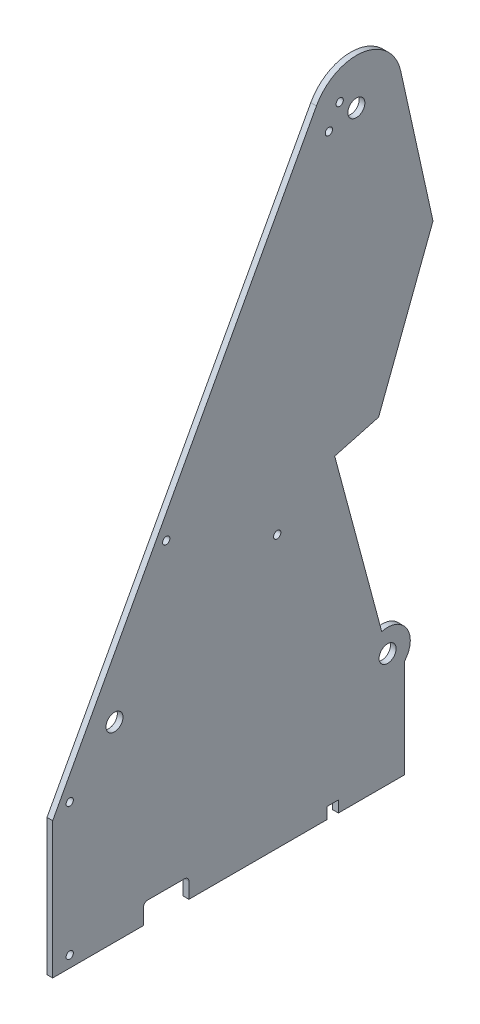
SolidWorks part; units mm, degrees
ref_plane "Front Plane" through (0, 0, 0) normal (0, 0, 1) x (1, 0, 0)
ref_plane "Top Plane" through (0, 0, 0) normal (0, 1, 0) x (1, 0, 0)
ref_plane "Right Plane" through (0, 0, 0) normal (1, 0, 0) x (0, 0, -1)
sketch "Sketch1" plane through (0, 0, 0) normal (1, 0, 0) x (0, 0, -1)
  line L0 (0, 0) -> (0, 55.0997)
  line L6 (-39.108, 173.9053) -> (-14.5735, 180.4793)
  line L7 (-14.5735, 180.4793) -> (15.875, 260.35)
  line L8 (15.875, 260.35) -> (-2.1865, 342.0339)
  line L9 (-49.3231, 348.6446) -> (-196.85, 76.2)
  line L10 (-196.85, 0) -> (0, 0)
  line L11 (-196.85, 76.2) -> (-196.85, 0)
  line L13 (-39.108, 173.9053) -> (-12.812, 75.7673)
  line L14 (-12.812, 75.7673) -> (13.738, 82.8813) construction
  arc A0 (-2.1865, 342.0339) -> (-49.3231, 348.6446) centre (-26.9875, 336.55) ccw
  arc A3 (0, 55.0997) -> (-12.812, 75.7673) centre (-9.525, 63.5) ccw
  dimension "D2" = 25.4
  dimension "D6" = 196.85
  dimension "D7" = 76.2
  dimension "D12" = 12.7
  dimension "D1" = 26.9875
  dimension "D3" = 336.55
  dimension "D4" = 25.4
  dimension "D5" = 101.6
  dimension "D10" = 9.525
  dimension "D11" = 63.5
  dimension "D13" = 76.2
  dimension "D14" = 15.875
  dimension "D15" = 15
extrude "Boss-Extrude1" add sketch "Sketch1" along normal blind 3.175
sketch "Sketch2" plane through (3.175, 0, 0) normal (1, 0, 0) x (0, 0, -1)
  line L16 (-146.05, 8.7909) -> (-146.05, -0.3034) construction
  line L17 (-123.0376, 11.1785) -> (-143.6624, 11.1785) construction
  line L18 (-120.65, -0.3034) -> (-120.65, 8.7909) construction
  line L19 (-146.05, 8.7909) -> (-146.05, 0)
  line L20 (-123.0376, 11.1785) -> (-143.6624, 11.1785)
  line L21 (-120.65, 0) -> (-120.65, 8.7909)
  line L23 (-37.0504, 0) -> (-37.0504, 6.35) construction
  line L24 (-43.4004, 0) -> (-37.0504, 0) construction
  line L25 (-146.05, 0) -> (-120.65, 0)
  line L26 (-196.85, 0) -> (0, 0) construction
  line L27 (-43.4004, 6.35) -> (-43.4004, 0) construction
  line L28 (-37.0504, 6.35) -> (-43.4004, 6.35) construction
  line L29 (-37.0504, 0) -> (-37.0504, 6.35)
  line L30 (-43.4004, 0) -> (-37.0504, 0)
  line L31 (-43.4004, 6.35) -> (-43.4004, 0)
  line L32 (-37.0504, 6.35) -> (-43.4004, 6.35)
  line L33 (-223.2996, 0) -> (-223.2996, 6.35) construction
  line L34 (-229.6496, 0) -> (-223.2996, 0) construction
  line L35 (-229.6496, 6.35) -> (-229.6496, 0) construction
  line L36 (-223.2996, 6.35) -> (-229.6496, 6.35) construction
  line L37 (-223.2996, 0) -> (-223.2996, 6.35)
  line L38 (-229.6496, 0) -> (-223.2996, 0)
  line L39 (-229.6496, 6.35) -> (-229.6496, 0)
  line L40 (-223.2996, 6.35) -> (-229.6496, 6.35)
  arc A0 (-143.6624, 11.1785) -> (-146.05, 8.7909) centre (-143.6624, 8.7909) ccw construction
  arc A1 (-120.65, 8.7909) -> (-123.0376, 11.1785) centre (-123.0376, 8.7909) ccw construction
  arc A2 (-143.6624, 11.1785) -> (-146.05, 8.7909) centre (-143.6624, 8.7909) ccw
  arc A3 (-120.65, 8.7909) -> (-123.0376, 11.1785) centre (-123.0376, 8.7909) ccw
extrude "Cut-Extrude1" cut sketch "Sketch2" against normal through all
sketch "Sketch3" plane through (3.175, 0, 0) normal (1, 0, 0) x (0, 0, -1)
  point P0 (-26.9875, 336.55)
  point P4 (-9.525, 63.5)
hole_wizard "3/8 Clearance Hole1" positions "Sketch3" profile "Sketch4" hole size "3/8" standard "ANSI Inch" end condition up to next
sketch "Sketch4" plane through (3.175, 336.55, 26.9875) normal (0, 1, 0) x (0, 0, -1)
  line L0 (0, 0) -> (0, 3.175)
  line L1 (0, 3.175) -> (4.7625, 3.175)
  line L2 (4.7625, 3.175) -> (4.7625, 0)
  line L5 (4.7625, 0) -> (0, 0)
  line L11 (0, -6.35) -> (0, 107.95) construction
  dimension "Thru Hole Dia." = 9.525
  dimension "Thru Hole Depth" = 3.175
sketch "Sketch5" plane through (3.175, 0, 0) normal (1, 0, 0) x (0, 0, -1)
  line L0 (-9.525, 63.5) -> (26.2895, 27.4728)
  line L1 (26.2895, 27.4728) -> (26.2524, 14.9296)
  line L2 (21.8127, 31.9762) -> (-24.8224, 22.3166)
  line L3 (-15.875, 19.05) -> (-24.8224, 22.3166)
  line L4 (0, 0) -> (0, 55.0997) construction
  line L5 (-15.875, 19.05) -> (-33.1481, 11.0161)
  line L6 (-33.1481, 11.0161) -> (-54.7505, 169.5016)
  line L7 (50.8, 0) -> (50.8, 73.5762) construction
  dimension "D1" = 44.45
  dimension "D2" = 50.8
  dimension "D3" = 45
  dimension "D4" = 60.325
  dimension "D5" = 19.05
  dimension "D6" = 15.875
  dimension "D7" = 9.525
  dimension "D8" = 47.625
  dimension "D9" = 19.05
  dimension "D10" = 45
  dimension "D11" = 50.8
sketch "Sketch6" plane through (3.175, 0, 0) normal (1, 0, 0) x (0, 0, -1)
  line L1 (-162.2756, 106.7109) -> (-176.2354, 114.27) construction
  line L3 (-49.3231, 348.6446) -> (-196.85, 76.2) construction
  circle A2 centre (-162.2756, 106.7109) radius 4.7625
  dimension "D4" = 9.525
  dimension "D5" = 15.875
  dimension "D6" = 266.7
extrude "Cut-Extrude2" cut sketch "Sketch6" against normal through all
sketch "Sketch8" [suppressed] plane through (3.175, 0, 0) normal (1, 0, 0) x (0, 0, -1)
  circle A0 centre (-159.5042, 86.429) radius 4.7625
  circle A1 centre (-165.9449, 66.9082) radius 2.032
  circle A2 centre (-112.0969, 96.3722) radius 2.032
  circle A3 centre (-165.9449, 66.9082) radius 1.905 construction
  circle A4 centre (-112.0969, 96.3722) radius 1.985 construction
  dimension "D1" = 25.4
  dimension "D2" = 9.525
  dimension "D3" = 4.064
extrude "Cut-Extrude3" [suppressed] cut sketch "Sketch8" against normal through all both and the other way through all
sketch "Sketch9" [suppressed] plane through (3.175, 0, 0) normal (1, 0, 0) x (0, 0, -1)
  circle A8 centre (-165.9449, 66.9082) radius 4.445
  circle A9 centre (-165.9449, 66.9082) radius 4.445
  dimension "D1" = 2.54
sketch "Sketch10" plane through (3.175, 0, 0) normal (1, 0, 0) x (0, 0, -1)
  circle A0 centre (-71.2566, 151.9429) radius 2.032
  dimension "D1" = 4.064
extrude "Cut-Extrude4" cut sketch "Sketch10" against normal through all
sketch "Sketch11" plane through (3.175, 0, 0) normal (1, 0, 0) x (0, 0, -1)
  circle A0 centre (-187.325, 80.4545) radius 2.032
  circle A1 centre (-187.325, 6.35) radius 2.032
  circle A2 centre (-187.325, 6.35) radius 2.032 construction
  circle A3 centre (-187.325, 80.4545) radius 2.032 construction
  dimension "D1" = 4.064
extrude "Cut-Extrude5" cut sketch "Sketch11" against normal through all
sketch "Sketch13" plane through (0, 0, 0) normal (-1, 0, 0) x (0, 0, 1)
  circle A0 centre (36.319, 343.9881) radius 2.032
  circle A1 centre (42.3663, 332.8203) radius 2.032
  circle A2 centre (36.319, 343.9881) radius 1.905 construction
  circle A3 centre (42.3663, 332.8203) radius 1.905 construction
  point P6 (0, 0)
  point P9 (0, 0)
  dimension "D1" = 4.064
extrude "Cut-Extrude6" cut sketch "Sketch13" against normal through all
sketch "Sketch14" plane through (3.175, 0, 0) normal (1, 0, 0) x (0, 0, -1)
  line L0 (-49.3231, 348.6446) -> (-196.85, 76.2) construction
  line L1 (-133.35, 180.1326) -> (-138.9339, 183.1563) construction
  circle A0 centre (-133.35, 180.1326) radius 2.032
  dimension "D1" = 4.064
  dimension "D2" = 6.35
  dimension "D3" = 133.35
extrude "Cut-Extrude7" cut sketch "Sketch14" against normal through all
